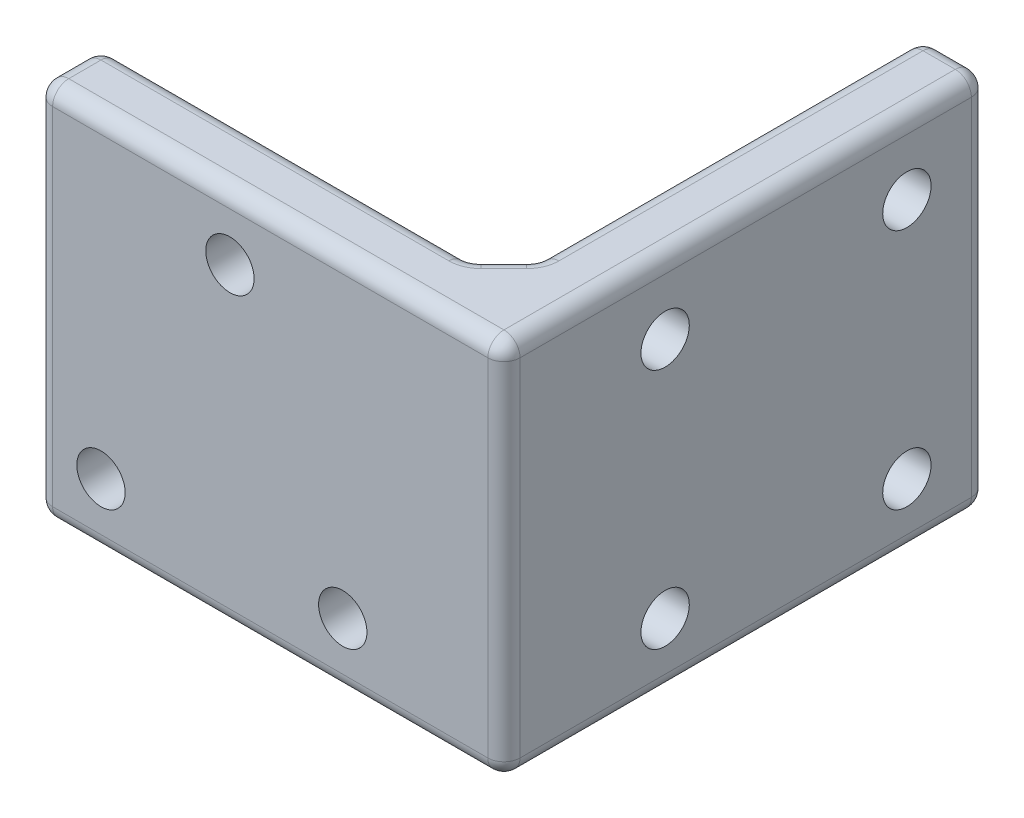
SolidWorks part; units mm, degrees
ref_plane "前视基准面" through (0, 0, 0) normal (0, 0, 1) x (1, 0, 0)
ref_plane "上视基准面" through (0, 0, 0) normal (0, 1, 0) x (1, 0, 0)
ref_plane "右视基准面" through (0, 0, 0) normal (1, 0, 0) x (0, 0, -1)
sketch "草图1" plane through (0, 0, 0) normal (0, 0, 1) x (1, 0, 0)
  line L1 (-9.5369, 14.9176) -> (15.4631, 14.9176)
  line L2 (-9.5369, 14.9176) -> (-9.5369, -8.5824)
  line L3 (-9.5369, -8.5824) -> (15.4631, -8.5824)
  line L4 (15.4631, 14.9176) -> (15.4631, -8.5824)
  circle A0 centre (2.4631, 10.9176) radius 1.5
  circle A1 centre (-5.5369, -4.5824) radius 1.5
  circle A2 centre (9.4631, -4.5824) radius 1.5
  dimension "D1" = 3
  dimension "D2" = 3
  dimension "D3" = 3
  dimension "D4" = 15
  dimension "D5" = 0
  dimension "D6" = 15.5
  dimension "D7" = 7
  dimension "D8" = 4
  dimension "D9" = 6
  dimension "D10" = 4
  dimension "D11" = 4
  dimension "D12" = 23.5
extrude "凸台-拉伸1" add sketch "草图1" along normal blind 4
sketch "草图2" plane through (15.4631, 0, 0) normal (1, 0, 0) x (0, 0, -1)
  line L0 (0, -8.5824) -> (0, 14.9176) construction
  line L1 (-4, 14.9176) -> (26, 14.9176)
  line L2 (-4, 14.9176) -> (-4, -8.5824)
  line L3 (-4, -8.5824) -> (26, -8.5824)
  line L4 (26, 14.9176) -> (26, -8.5824)
  circle A0 centre (6, 10.4176) radius 1.5
  circle A1 centre (21, 10.4176) radius 1.5
  circle A2 centre (6, -4.5824) radius 1.5
  circle A3 centre (21, -4.5824) radius 1.5
  dimension "D9" = 3
  dimension "D10" = 3
  dimension "D11" = 3
  dimension "D12" = 3
  dimension "D1" = 23.5
  dimension "D2" = 30
  dimension "D3" = 15
  dimension "D4" = 15
  dimension "D5" = 15
  dimension "D6" = 15
  dimension "D7" = 15
  dimension "D8" = 15
  dimension "D13" = 4.5
  dimension "D14" = 4
  dimension "D15" = 6
  dimension "D16" = 5
extrude "凸台-拉伸2" add sketch "草图2" along normal blind 4
chamfer "倒角1" distance 2 angle 45 1 edges at (15.4631, 3.1676, 0)
fillet "圆角1" radius 1 21 edges at (-9.5369, 3.1676, 0) (-9.5369, 3.1676, 4) (19.4631, 14.9176, -11) (4.9631, 14.9176, 4) (-9.5369, 14.9176, 2) (1.9631, 14.9176, 0) (15.4631, 14.9176, -14) (-9.5369, -8.5824, 2) (4.9631, -8.5824, 4) (19.4631, -8.5824, -11) (15.4631, -8.5824, -14) (1.9631, -8.5824, 0) (17.4631, -8.5824, -26) (19.4631, 3.1676, -26) (17.4631, 14.9176, -26) (15.4631, 3.1676, -26) (15.4631, 3.1676, -2) (14.4631, 14.9176, -1) (13.4631, 3.1676, 0) (14.4631, -8.5824, -1) (19.4631, 3.1676, 4)
